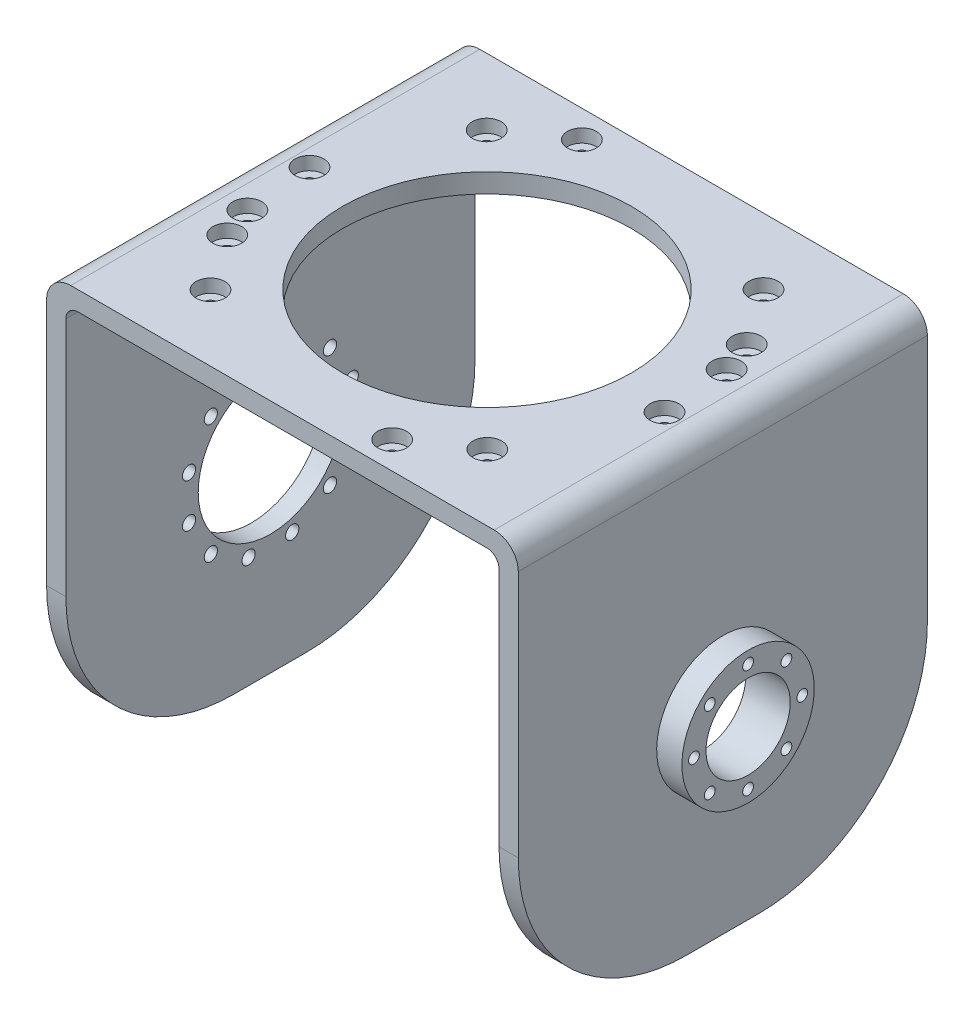
SolidWorks part; units mm, degrees
material "6061 合金"
ref_plane "前视基准面" through (0, 0, 0) normal (0, 0, 1) x (1, 0, 0)
ref_plane "上视基准面" through (0, 0, 0) normal (0, 1, 0) x (1, 0, 0)
ref_plane "右视基准面" through (0, 0, 0) normal (1, 0, 0) x (0, 0, -1)
other "Configuration Table"
sketch "草图1" plane through (0, 0, 0) normal (0, 0, 1) x (1, 0, 0)
  line L0 (-180, 0) -> (0, 0)
  line L1 (0, 0) -> (0, -175)
  line L3 (8, -175) -> (8, 8)
  line L4 (8, 8) -> (-180, 8)
  line L6 (0, -175) -> (8, -175)
  line L12 (-180, 8) -> (-188, 8)
  line L13 (-180, 0) -> (-180, -175)
  line L14 (-180, -175) -> (-188, -175)
  line L15 (-188, 8) -> (-188, -175)
  dimension "D1" = 8
  dimension "D2" = 8
  dimension "D4" = 180
  dimension "D5" = 183
  dimension "D6" = 8
  dimension "D8" = 8
extrude "凸台-拉伸1" add sketch "草图1" along normal blind 170
sketch "草图2" plane through (0, 8, 0) normal (0, 1, 0) x (1, 0, 0)
  line L0 (-216.3195, -85) -> (51.5119, -85) construction
  line L1 (8, -170) -> (-188, -170) construction
  line L2 (8, 0) -> (-188, 0) construction
  line L7 (-90, -75.3242) -> (-90, -92.2023) construction
  line L8 (8, -170) -> (8, 0) construction
  line L9 (-188, -170) -> (-188, 0) construction
  circle A2 centre (-90, -85) radius 60
  dimension "D3" = 120
extrude "切除-拉伸1" cut sketch "草图2" against normal blind 180 contours A2 L0 | L0 A2
sketch "草图3" plane through (8, 0, 0) normal (1, 0, 0) x (0, 0, -1)
  line L0 (-85, 25.6845) -> (-85, -173.3318) construction
  line L1 (0, -175) -> (0, 8) construction
  line L2 (-170, -175) -> (-170, 8) construction
  line L3 (-170, -175) -> (0, -175) construction
  line L4 (0, 0) -> (-209.686, 0) construction
  circle A0 centre (-85, -95) radius 17.5
  dimension "D1" = 35
  dimension "D2" = 80
extrude "切除-拉伸2" cut sketch "草图3" against normal through all both and the other way through all contours A0
fillet "圆角1" radius 70 4 edges at (-184, -175, 170) (-184, -175, 0) (4, -175, 0) (4, -175, 170)
fillet "圆角2" radius 5 2 edges at (-180, 0, 85) (0, 0, 85)
fillet "圆角3" radius 10 2 edges at (8, 8, 85) (-188, 8, 85)
sketch "草图6" plane through (-188, 0, 0) normal (-1, 0, 0) x (0, 0, 1)
  circle A0 centre (85, -95) radius 30
  dimension "D1" = 60
extrude "切除-拉伸6" cut sketch "草图6" against normal blind 39
sketch "草图7" plane through (0, 0, 0) normal (-1, 0, 0) x (0, 0, 1)
  circle A0 centre (85, -95) radius 13
  dimension "D1" = 26
extrude "切除-拉伸7" [suppressed] cut sketch "草图7" against normal blind 0.7
sketch "草图8" plane through (8, 0, 0) normal (1, 0, 0) x (0, 0, -1)
  line L0 (-85, -95) -> (-13.3452, -95) construction
  line L1 (-85, -95) -> (-143.0331, -95) construction
  circle A0 centre (-55, -95) radius 2.5
  circle A1 centre (-115, -95) radius 2.5
  dimension "D1" = 5
  dimension "D2" = 5
  dimension "D3" = 30
  dimension "D4" = 30
extrude "切除-拉伸8" [suppressed] cut sketch "草图8" against normal blind 10
sketch "草图9" [suppressed] plane through (8, 0, 0) normal (1, 0, 0) x (0, 0, -1)
  circle A0 centre (-55, -95) radius 6
  circle A1 centre (-115, -95) radius 6
  dimension "D1" = 12
  dimension "D2" = 12
extrude "切除-拉伸9" [suppressed] cut sketch "草图9" against normal blind 4
sketch "草图10" plane through (0, 0, 0) normal (0, -1, 0) x (1, 0, 0)
  arc A0 (-173.1989, 76.7742) -> (-168.6673, 78.8872) centre (-170.9331, 77.8307) ccw construction
  arc A1 (-149.7806, 26.5535) -> (-145.249, 28.6665) centre (-147.5148, 27.61) ccw construction
  arc A2 (-126.5235, 10.2687) -> (-121.992, 12.3818) centre (-124.2577, 11.3252) ccw construction
  arc A3 (-113.38, 5.4849) -> (-108.8485, 7.598) centre (-111.1143, 6.5414) ccw construction
  arc A4 (-85.0965, 3.0104) -> (-80.5649, 5.1235) centre (-82.8307, 4.0669) ccw construction
  arc A5 (-34.8758, 26.4287) -> (-30.3442, 28.5418) centre (-32.61, 27.4852) ccw construction
  arc A6 (-13.8072, 62.8292) -> (-9.2756, 64.9423) centre (-11.5414, 63.8857) ccw construction
  arc A7 (-18.591, 49.6857) -> (-14.0595, 51.7988) centre (-16.3252, 50.7423) ccw construction
  arc A8 (-6.8011, 93.2258) -> (-11.3327, 91.1128) centre (-9.0669, 92.1693) ccw construction
  arc A9 (-30.2194, 143.4465) -> (-34.751, 141.3335) centre (-32.4852, 142.39) ccw construction
  arc A10 (-53.4765, 159.7313) -> (-58.008, 157.6182) centre (-55.7423, 158.6748) ccw construction
  arc A11 (-66.62, 164.5151) -> (-71.1515, 162.402) centre (-68.8857, 163.4586) ccw construction
  arc A12 (-94.9035, 166.9896) -> (-99.4351, 164.8765) centre (-97.1693, 165.9331) ccw construction
  arc A13 (-145.1242, 143.5713) -> (-149.6558, 141.4582) centre (-147.39, 142.5148) ccw construction
  arc A14 (-161.409, 120.3143) -> (-165.9405, 118.2012) centre (-163.6748, 119.2577) ccw construction
  arc A15 (-166.1928, 107.1708) -> (-170.7244, 105.0577) centre (-168.4586, 106.1143) ccw construction
  arc A16 (-173.1989, 76.7742) -> (-168.6673, 78.8872) centre (-170.9331, 77.8307) ccw construction
  arc A17 (-149.7806, 26.5535) -> (-145.249, 28.6665) centre (-147.5148, 27.61) ccw construction
  arc A18 (-126.5235, 10.2687) -> (-121.992, 12.3818) centre (-124.2577, 11.3252) ccw construction
  arc A19 (-113.38, 5.4849) -> (-108.8485, 7.598) centre (-111.1143, 6.5414) ccw construction
  arc A20 (-85.0965, 3.0104) -> (-80.5649, 5.1235) centre (-82.8307, 4.0669) ccw construction
  arc A21 (-34.8758, 26.4287) -> (-30.3442, 28.5418) centre (-32.61, 27.4852) ccw construction
  arc A22 (-13.8072, 62.8292) -> (-9.2756, 64.9423) centre (-11.5414, 63.8857) ccw construction
  arc A23 (-18.591, 49.6857) -> (-14.0595, 51.7988) centre (-16.3252, 50.7423) ccw construction
  arc A24 (-6.8011, 93.2258) -> (-11.3327, 91.1128) centre (-9.0669, 92.1693) ccw construction
  arc A25 (-30.2194, 143.4465) -> (-34.751, 141.3335) centre (-32.4852, 142.39) ccw construction
  arc A26 (-53.4765, 159.7313) -> (-58.008, 157.6182) centre (-55.7423, 158.6748) ccw construction
  arc A27 (-66.62, 164.5151) -> (-71.1515, 162.402) centre (-68.8857, 163.4586) ccw construction
  arc A28 (-94.9035, 166.9896) -> (-99.4351, 164.8765) centre (-97.1693, 165.9331) ccw construction
  arc A29 (-145.1242, 143.5713) -> (-149.6558, 141.4582) centre (-147.39, 142.5148) ccw construction
  arc A30 (-161.409, 120.3143) -> (-165.9405, 118.2012) centre (-163.6748, 119.2577) ccw construction
  arc A31 (-166.1928, 107.1708) -> (-170.7244, 105.0577) centre (-168.4586, 106.1143) ccw construction
  circle A32 centre (-32.4852, 142.39) radius 2.5
  circle A33 centre (-55.7423, 158.6748) radius 2.5
  circle A34 centre (-68.8857, 163.4586) radius 2.5
  circle A35 centre (-147.39, 142.5148) radius 2.5
  circle A36 centre (-163.6748, 119.2577) radius 2.5
  circle A37 centre (-168.4586, 106.1143) radius 2.5
  circle A38 centre (-170.9331, 77.8307) radius 2.5
  circle A40 centre (-147.5148, 27.61) radius 2.5
  circle A41 centre (-124.2577, 11.3252) radius 2.5
  circle A42 centre (-111.1143, 6.5414) radius 2.5
  circle A44 centre (-32.61, 27.4852) radius 2.5
  circle A45 centre (-16.3252, 50.7423) radius 2.5
  circle A46 centre (-11.5414, 63.8857) radius 2.5
  circle A47 centre (-9.0669, 92.1693) radius 2.5
  dimension "D1" = 5
extrude "切除-拉伸10" cut sketch "草图10" against normal blind 10 contours A33 | A32 | A47 | A46 | A45 | A44 | A41 | A40 | A38 | A37 | A36 | A35
sketch "草图11" plane through (0, 8, 0) normal (0, 1, 0) x (1, 0, 0)
  circle A1 centre (-32.61, -27.4852) radius 6
  circle A2 centre (-16.3252, -50.7423) radius 6
  circle A3 centre (-11.5414, -63.8857) radius 6
  circle A4 centre (-9.0669, -92.1693) radius 6
  circle A5 centre (-32.4852, -142.39) radius 6
  circle A6 centre (-55.7423, -158.6748) radius 6
  circle A8 centre (-147.39, -142.5148) radius 6
  circle A9 centre (-163.6748, -119.2577) radius 6
  circle A10 centre (-168.4586, -106.1143) radius 6
  circle A11 centre (-170.9331, -77.8307) radius 6
  circle A12 centre (-147.5148, -27.61) radius 6
  circle A13 centre (-124.2577, -11.3252) radius 6
  circle M2 centre (-55.7423, -158.6748) radius 2.5
  circle M4 centre (-147.39, -142.5148) radius 2.5
  circle M5 centre (-163.6748, -119.2577) radius 2.5
  circle M6 centre (-168.4586, -106.1143) radius 2.5
  circle M7 centre (-170.9331, -77.8307) radius 2.5
  circle M8 centre (-147.5148, -27.61) radius 2.5
  circle M9 centre (-124.2577, -11.3252) radius 2.5
  circle M11 centre (-32.61, -27.4852) radius 2.5
  circle M12 centre (-16.3252, -50.7423) radius 2.5
  circle M13 centre (-11.5414, -63.8857) radius 2.5
  circle M14 centre (-9.0669, -92.1693) radius 2.5
  circle M15 centre (-32.4852, -142.39) radius 2.5
  dimension "D1" = 12
extrude "切除-拉伸11" cut sketch "草图11" against normal blind 5.5 contours A5 M15 | A6 M2 | A8 M4 | A9 M5 | A10 M6 | A11 M7 | A12 M8 | A13 M9 | A1 M11 | A2 M12 | A3 M13 | A4 M14
sketch "草图12" plane through (-188, 0, 0) normal (-1, 0, 0) x (0, 0, 1)
  line L0 (85, -95) -> (85, -143.8801) construction
  line L1 (85, -95) -> (97.9809, -143.4455) construction
  circle A0 centre (94.0587, -128.8074) radius 2.75
  circle A1 centre (75.9413, -128.8074) radius 2.75
  circle A2 centre (60.2513, -119.7487) radius 2.75
  circle A3 centre (51.1926, -104.0587) radius 2.75
  circle A4 centre (51.1926, -85.9413) radius 2.75
  circle A5 centre (60.2513, -70.2513) radius 2.75
  circle A6 centre (75.9413, -61.1926) radius 2.75
  circle A7 centre (94.0587, -61.1926) radius 2.75
  circle A8 centre (109.7487, -70.2513) radius 2.75
  circle A9 centre (118.8074, -85.9413) radius 2.75
  circle A10 centre (118.8074, -104.0587) radius 2.75
  circle A11 centre (109.7487, -119.7487) radius 2.75
  point P31 (85, -95)
  dimension "D2" = 5.5
  dimension "D1" = 15
  dimension "D3" = 35
  dimension "D4" = 12
extrude "切除-拉伸12" cut sketch "草图12" against normal blind 10
sketch "草图14" plane through (8, 0, 0) normal (1, 0, 0) x (0, 0, -1)
  circle A0 centre (-85, -95) radius 27.5
  circle A1 centre (-85, -95) radius 17.5 construction
  circle A2 centre (-85, -95) radius 17.5
  dimension "D1" = 55
extrude "凸台-拉伸2" add sketch "草图14" along normal blind 10.5
sketch "草图13" plane through (8, 0, 0) normal (1, 0, 0) x (0, 0, -1)
  line L0 (-85, -95) -> (-85, -50) construction
  circle A0 centre (-85, -95) radius 22.5 construction
  circle A1 centre (-85, -72.5) radius 2.25
  circle A2 centre (-69.0901, -79.0901) radius 2.25
  circle A3 centre (-62.5, -95) radius 2.25
  circle A4 centre (-69.0901, -110.9099) radius 2.25
  circle A5 centre (-85, -117.5) radius 2.25
  circle A6 centre (-100.9099, -110.9099) radius 2.25
  circle A7 centre (-107.5, -95) radius 2.25
  circle A8 centre (-100.9099, -79.0901) radius 2.25
  point P22 (-85, -95)
  dimension "D1" = 45
  dimension "D2" = 4.5
  dimension "D3" = 8
extrude "切除-拉伸13" cut sketch "草图13" against normal mid plane 30
